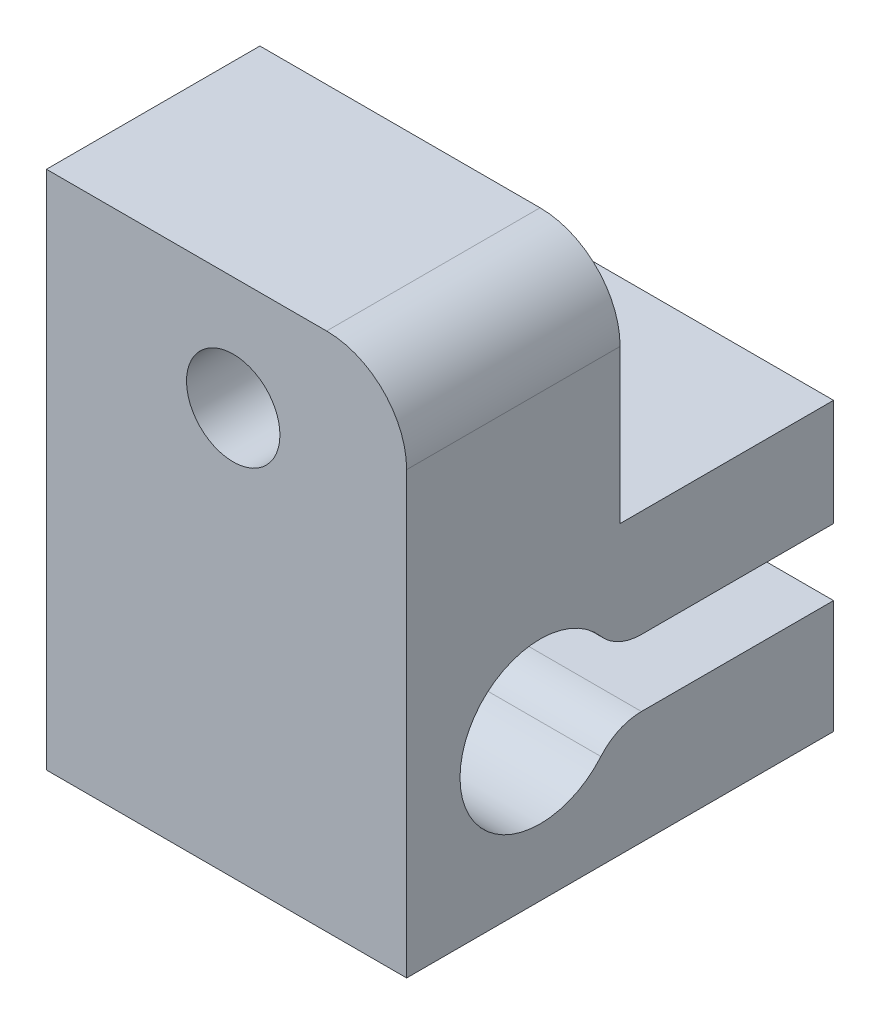
SolidWorks part; units mm, degrees
ref_plane "Front Plane" through (0, 0, 0) normal (0, 0, 1) x (1, 0, 0)
ref_plane "Top Plane" through (0, 0, 0) normal (0, 1, 0) x (1, 0, 0)
ref_plane "Right Plane" through (0, 0, 0) normal (1, 0, 0) x (0, 0, -1)
sketch "Sketch1" plane through (0, 0, 0) normal (1, 0, 0) x (0, 0, -1)
  line L1 (-8, -9.75) -> (8, -9.75)
  line L2 (-8, -9.75) -> (-8, 9.75)
  line L3 (-8, 9.75) -> (8, 9.75)
  line L4 (8, -9.75) -> (8, 9.75)
  line L5 (-8, -9.75) -> (8, 9.75) construction
  line L6 (-8, 9.75) -> (8, -9.75) construction
  line L7 (8, 9.75) -> (0, 9.75)
  line L8 (8, 9.75) -> (8, 1)
  line L9 (8, 1) -> (0, 1)
  line L10 (0, 9.75) -> (0, 1)
  point P0 (0, 0)
  dimension "D1" = 16
  dimension "D2" = 19.5
  dimension "D3" = 8
  dimension "D4" = 8.75
extrude "Boss-Extrude1" add sketch "Sketch1" along normal blind 13.5 contours L10 L3 L2 L1 L4 L9
sketch "Sketch2" plane through (13.5, 0, 0) normal (1, 0, 0) x (0, 0, -1)
  line L0 (-8, -9.75) -> (8, -9.75) construction
  line L1 (8, -9.75) -> (8, 1) construction
  line L2 (-3, -3) -> (8, -3)
  line L3 (-3, -3) -> (-3, -5.5)
  line L4 (-3, -5.5) -> (8, -5.5)
  line L5 (8, -3) -> (8, -5.5)
  circle A0 centre (-3, -4.25) radius 3
  dimension "D2" = 6
  dimension "D1" = 5.5
  dimension "D3" = 2.5
  dimension "D4" = 1.25
  dimension "D5" = 11
  dimension "D6" = 11
extrude "Cut-Extrude1" cut sketch "Sketch2" against normal blind 9 contours L2 A0 L4 L3 | L4 A0 L2 L3
sketch "Sketch3" plane through (4.5, 0, 0) normal (1, 0, 0) x (0, 0, -1)
  arc A0 (-0.2728, -3) -> (-0.2728, -5.5) centre (-3, -4.25) ccw construction
  arc A1 (-0.2728, -3) -> (-0.2728, -5.5) centre (-3, -4.25) ccw
  circle A2 centre (-3, -4.25) radius 1.75
  dimension "D1" = 3.5
extrude "Cut-Extrude2" cut sketch "Sketch3" against normal through all both and the other way through all contours A2
sketch "Sketch4" plane through (0, 0, 0) normal (-1, 0, 0) x (0, 0, 1)
  line L1 (6.1754, -4.25) -> (4.5877, -1.5)
  line L2 (4.5877, -1.5) -> (1.4123, -1.5)
  line L3 (1.4123, -1.5) -> (-0.1754, -4.25)
  line L4 (-0.1754, -4.25) -> (1.4123, -7)
  line L5 (1.4123, -7) -> (4.5877, -7)
  line L6 (4.5877, -7) -> (6.1754, -4.25)
  circle A0 centre (3, -4.25) radius 1.75 construction
  circle A1 centre (3, -4.25) radius 1.75
  circle A2 centre (3, -4.25) radius 2.75 construction
  dimension "D1" = 5.5
extrude "Cut-Extrude4" cut sketch "Sketch4" against normal blind 2.5
sketch "Sketch5" plane through (0, 0, 0) normal (0, 0, -1) x (-1, 0, 0)
  line L0 (0, 9.75) -> (0, 1) construction
  line L1 (-13.5, 1) -> (0, 1) construction
  circle A0 centre (-7, 5.5) radius 1.75
  dimension "D3" = 3.5
  dimension "D1" = 7
  dimension "D2" = 4.5
extrude "Cut-Extrude5" cut sketch "Sketch5" against normal through all
sketch "Sketch6" plane through (0, 0, 0) normal (0, 0, -1) x (-1, 0, 0)
  circle A0 centre (-7, 5.5) radius 1.75 construction
  circle A1 centre (-7, 5.5) radius 1.75
  circle A2 centre (-7, 5.5) radius 3
  dimension "D1" = 6
extrude "Cut-Extrude6" cut sketch "Sketch6" against normal blind 5
fillet "Fillet1" radius 3 1 edges at (13.5, 9.75, 4)
fillet "Fillet2" radius 2 2 edges at (9, -5.5, 0.2728) (9, -3, 0.2728)
